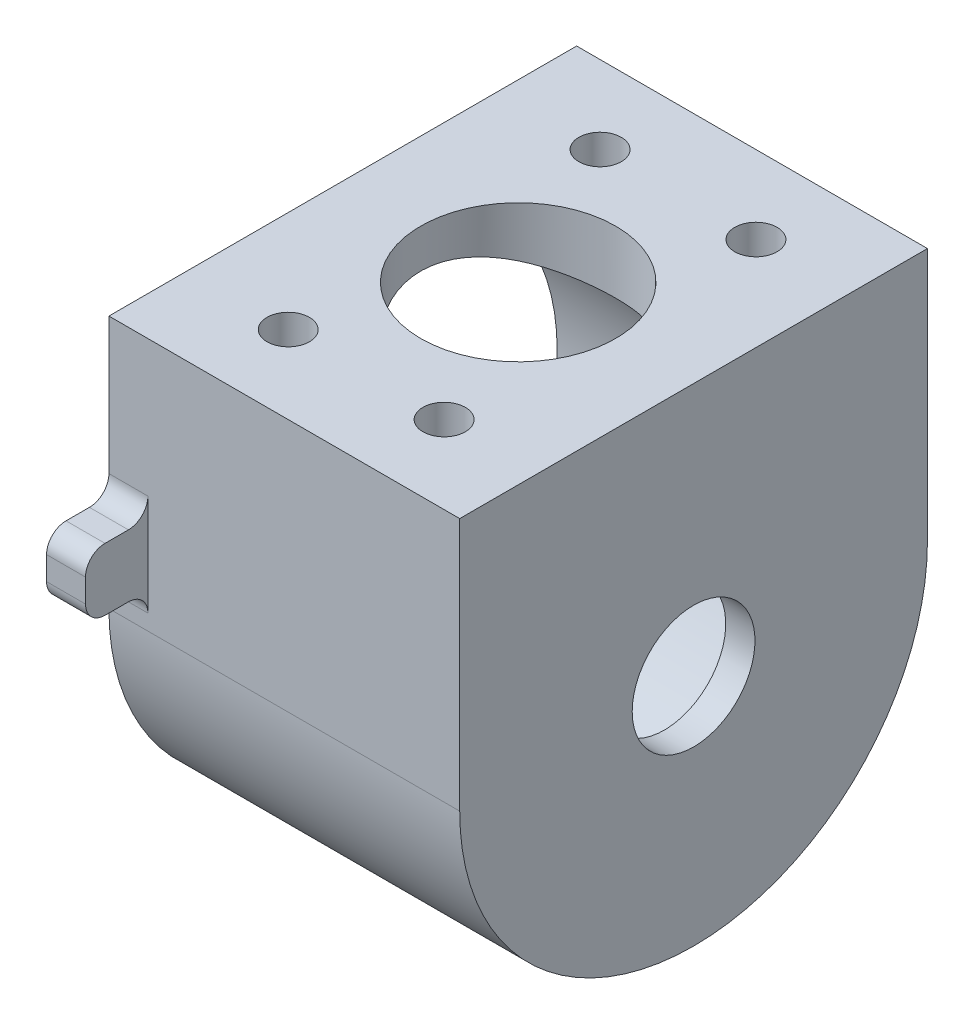
SolidWorks part; units mm, degrees
material "6061-T6 (SS)"
ref_plane "Front Plane" through (0, 0, 0) normal (0, 0, 1) x (1, 0, 0)
ref_plane "Top Plane" through (0, 0, 0) normal (0, 1, 0) x (1, 0, 0)
ref_plane "Right Plane" through (0, 0, 0) normal (1, 0, 0) x (0, 0, -1)
sketch "Sketch1" plane through (0, 0, 0) normal (1, 0, 0) x (0, 0, -1)
  line L2 (-19.05, 0) -> (-19.05, 20.6375)
  line L3 (-19.05, 20.6375) -> (19.05, 20.6375)
  line L4 (19.05, 0) -> (19.05, 20.6375)
  line L5 (-19.05, -20.6375) -> (19.05, 20.6375) construction
  line L6 (-19.05, 20.6375) -> (19.05, -20.6375) construction
  circle A0 centre (0, 0) radius 17.4625 construction
  arc A1 (-19.05, 0) -> (19.05, 0) centre (0, 0) ccw
  dimension "D1" = 34.925
  dimension "D4" = 19.05
  dimension "D2" = 38.1
  dimension "D3" = 41.275
extrude "Boss-Extrude1" add sketch "Sketch1" along normal blind 28.575
sketch "Sketch2" plane through (0, 0, 0) normal (-1, 0, 0) x (0, 0, 1)
  circle A0 centre (0, 0) radius 17.4625
  dimension "D1" = 34.925
extrude "Cut-Extrude1" cut sketch "Sketch2" against normal blind 26.1937
sketch "Sketch3" plane through (26.1937, 0, 0) normal (-1, 0, 0) x (0, 0, 1)
  circle A0 centre (0, 0) radius 5
  dimension "D1" = 10
extrude "Cut-Extrude2" cut sketch "Sketch3" against normal through all
hole_wizard "#8-32 Tapped Hole1" positions "Sketch5" profile "Sketch4" tap size "#8-32" standard "Ansi Inch"
sketch "Sketch5" plane through (0, 20.6375, 0) normal (0, 1, 0) x (-1, 0, 0)
  line L0 (-28.575, -19.05) -> (-28.575, 19.05) construction
  point P0 (-8.255, 12.7)
  point P1 (-8.255, -12.7)
  point P3 (-20.955, -12.7)
  point P6 (-20.955, 12.7)
  point P21 (-34.2582, 14.4282)
  dimension "D1" = 25.4
  dimension "D2" = 12.7
  dimension "D3" = 12.7
  dimension "D4" = 7.62
sketch "Sketch4" plane through (8.255, 20.6375, 12.7) normal (1, 0, 0) x (0, 0, 1)
  line L0 (0, 0) -> (0, 6.6258)
  line L1 (0, 6.6258) -> (1.7272, 5.588)
  line L2 (1.7272, 5.588) -> (1.7272, 0)
  line L5 (1.7272, 0) -> (0, 0)
  line L10 (0, 6.6258) -> (-1.7272, 5.588) construction
  line L11 (0, -6.35) -> (0, 107.95) construction
  dimension "Tap Drill Dia." = 3.4544
  dimension "Tap Drill Depth" = 5.588
  dimension "Drill Angle" = 118
cosmetic thread "Hole Thread1" parameters "D1"=5.588, "D2"=4.1656
cosmetic thread "Hole Thread2" parameters "D1"=5.588, "D2"=4.1656
cosmetic thread "Hole Thread3" parameters "D1"=5.588, "D2"=4.1656
cosmetic thread "Hole Thread4" parameters "D1"=5.588, "D2"=4.1656
sketch "Sketch6" plane through (0, 0, 0) normal (-1, 0, 0) x (0, 0, 1)
  line L0 (-19.05, 20.6375) -> (19.05, 20.6375) construction
  line L1 (-19.05, 2.8575) -> (-24.13, 2.8575)
  line L2 (-19.05, 2.8575) -> (-19.05, 7.9375)
  line L3 (-19.05, 7.9375) -> (-24.13, 7.9375)
  line L4 (-24.13, 2.8575) -> (-24.13, 7.9375)
  line L5 (-19.05, 0) -> (-19.05, 20.6375) construction
  line L6 (0, 0) -> (-24.13, 2.8575) construction
  dimension "D1" = 5.08
  dimension "D2" = 5.08
  dimension "D3" = 12.7
extrude "Boss-Extrude2" add sketch "Sketch6" against normal blind 3.175
mirror "Mirror1" about plane through (0, 0, 0) normal (0, 0, 1) of "Boss-Extrude2"
fillet "Fillet1" radius 1.5875 8 edges at (1.5875, 7.9375, -19.05) (1.5875, 7.9375, -24.13) (1.5875, 2.8575, -24.13) (1.5875, 2.8575, -19.05) (1.5875, 7.9375, 19.05) (1.5875, 7.9375, 24.13) (1.5875, 2.8575, 24.13) (1.5875, 2.8575, 19.05)
sketch "Sketch7" plane through (0, 20.6375, 0) normal (0, 1, 0) x (1, 0, 0)
  line L0 (14.2875, 19.05) -> (14.2875, -19.05) construction
  line L1 (28.575, 19.05) -> (0, 19.05) construction
  line L2 (28.575, -19.05) -> (0, -19.05) construction
  circle A0 centre (14.2875, 0) radius 7.9375
  dimension "D1" = 15.875
extrude "Cut-Extrude3" cut sketch "Sketch7" against normal up to next
